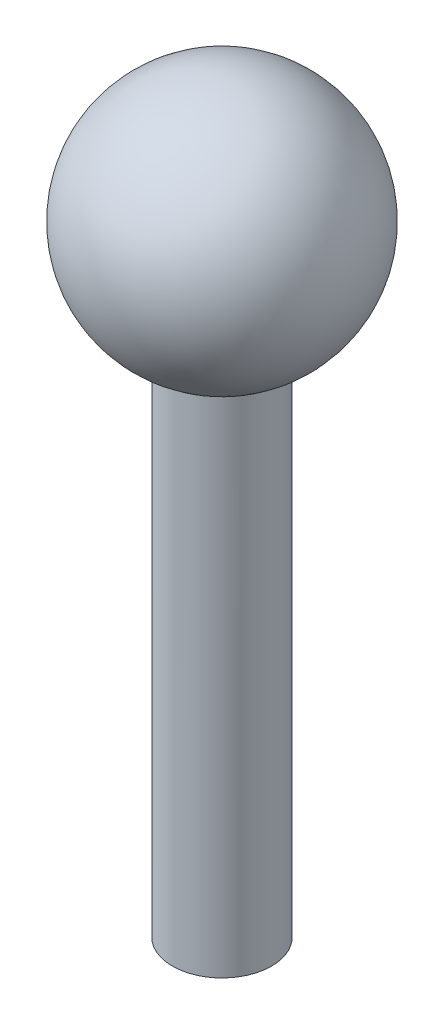
SolidWorks part; units mm, degrees
ref_plane "Front Plane" through (0, 0, 0) normal (0, 0, 1) x (1, 0, 0)
ref_plane "Top Plane" through (0, 0, 0) normal (0, 1, 0) x (1, 0, 0)
ref_plane "Right Plane" through (0, 0, 0) normal (1, 0, 0) x (0, 0, -1)
sketch "Sketch1" plane through (0, 0, 0) normal (0, 0, 1) x (1, 0, 0)
  line L0 (0, 0) -> (-4, 0)
  line L1 (-4, 0) -> (-4, 40.8348)
  line L16 (0, 0) -> (0, 60)
  arc A0 (0, 60) -> (-4, 40.8348) centre (0, 50) ccw
  dimension "10" = 20
  dimension "D2" = 60
  dimension "D3" = 4
revolve "Revolve1" add sketch "Sketch1" angle 360 about L16
sketch "Sketch2" plane through (0, 0, 0) normal (0, -1, 0) x (-1, 0, 0)
  circle A0 centre (0, 0) radius 5
  circle A1 centre (0, -22) radius 5
  circle A2 centre (0, 22) radius 5
  dimension "D1" = 10
  dimension "D3" = 10
  dimension "D4" = 10
  dimension "D2" = 22
  dimension "D5" = 22
sketch "Sketch3" plane through (0, 100, 0) normal (0, 1, 0) x (1, 0, 0)
  circle A0 centre (0, 0) radius 31
  circle A1 centre (0, 0) radius 31 construction
